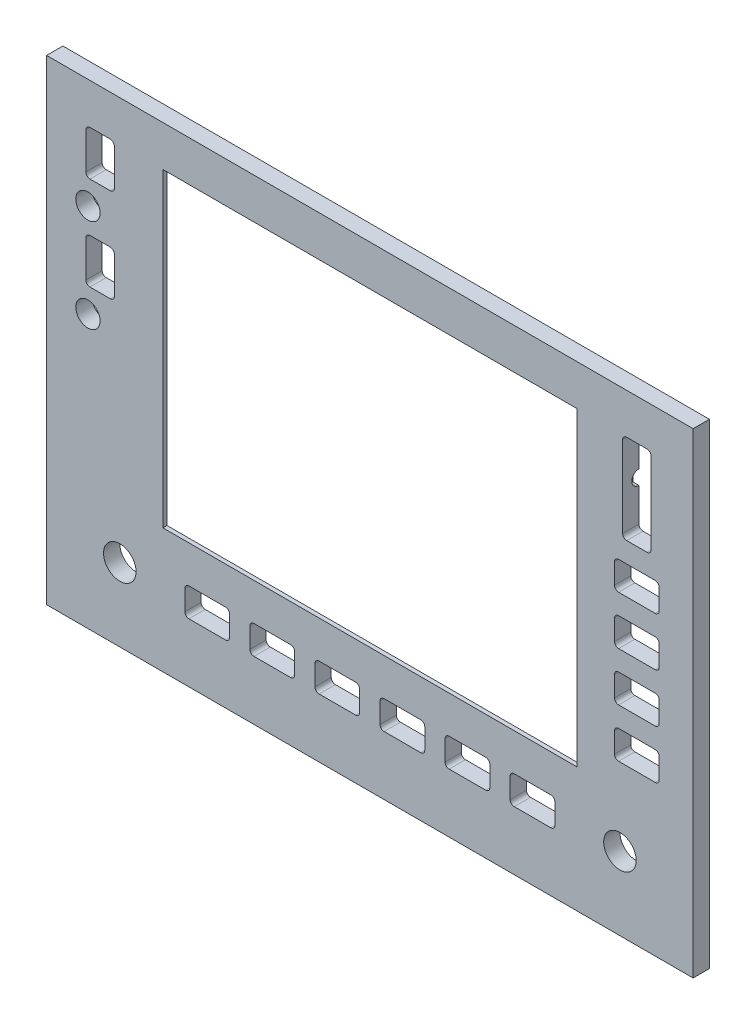
SolidWorks part; units mm, degrees
ref_plane "Plan de face" through (0, 0, 0) normal (0, 0, 1) x (1, 0, 0)
ref_plane "Plan de dessus" through (0, 0, 0) normal (0, 1, 0) x (1, 0, 0)
ref_plane "Plan de droite" through (0, 0, 0) normal (1, 0, 0) x (0, 0, -1)
sketch "Esquisse1" plane through (0, 0, 0) normal (0, 0, 1) x (1, 0, 0)
  line L1 (0, 0) -> (159, 0)
  line L2 (0, 0) -> (0, 117)
  line L3 (0, 117) -> (159, 117)
  line L4 (159, 0) -> (159, 117)
  dimension "D1" = 159
  dimension "D2" = 117
extrude "Boss.-Extru.1" add sketch "Esquisse1" along normal blind 4
sketch "Esquisse3" plane through (0, 0, 4) normal (0, 0, 1) x (1, 0, 0)
  line L1 (28.62, 107) -> (130.38, 107)
  line L2 (28.62, 107) -> (28.62, 30.68)
  line L3 (28.62, 30.68) -> (130.38, 30.68)
  line L4 (130.38, 107) -> (130.38, 30.68)
  line L7 (159, 0) -> (159, 117) construction
  line L8 (0, 117) -> (0, 0) construction
  line L9 (159, 117) -> (0, 117) construction
  dimension "D1" = 101.76
  dimension "D2" = 76.32
  dimension "D3" = 28.62
  dimension "D4" = 28.62
  dimension "D5" = 10
extrude "Enlèv. mat.-Extru.2" cut sketch "Esquisse3" against normal blind 4
sketch "Esquisse9" plane through (0, 0, 0) normal (0, 0, -1) x (-1, 0, 0)
  line L1 (-138.164, 111.6266) -> (-20.164, 111.6266)
  line L2 (-138.164, 111.6266) -> (-138.164, 22.7266)
  line L3 (-138.164, 22.7266) -> (-20.164, 22.7266)
  line L4 (-20.164, 111.6266) -> (-20.164, 22.7266)
  dimension "D5" = 118
  dimension "D6" = 88.9
extrude "Enlèv. mat.-Extru.5" cut sketch "Esquisse9" against normal blind 3
sketch "Esquisse4" plane through (0, 0, 4) normal (0, 0, 1) x (1, 0, 0)
  line L1 (159, 0) -> (159, 117) construction
  line L3 (0, 117) -> (0, 0) construction
  line L4 (0, 0) -> (159, 0) construction
  circle A0 centre (141, 18) radius 4
  circle A1 centre (18, 18) radius 4
  dimension "D1" = 8
  dimension "D2" = 8
  dimension "D3" = 18
  dimension "D4" = 18
  dimension "D5" = 18
  dimension "D6" = 18
extrude "Enlèv. mat.-Extru.3" cut sketch "Esquisse4" against normal blind 4
sketch "Esquisse10" plane through (0, 0, 0) normal (0, 0, -1) x (-1, 0, 0)
  line L0 (-172.9105, 18) -> (39.4334, 18) construction
  line L1 (-159, 0) -> (-159, 117) construction
  line L2 (-124, 21.5) -> (-115, 21.5)
  line L3 (-125, 20.5) -> (-125, 15.5)
  line L4 (-124, 14.5) -> (-115, 14.5)
  line L5 (-114, 20.5) -> (-114, 15.5)
  line L6 (-108, 21.5) -> (-99, 21.5)
  line L7 (-109, 20.5) -> (-109, 15.5)
  line L8 (-108, 14.5) -> (-99, 14.5)
  line L9 (-98, 20.5) -> (-98, 15.5)
  line L10 (-92, 21.5) -> (-83, 21.5)
  line L11 (-93, 20.5) -> (-93, 15.5)
  line L12 (-92, 14.5) -> (-83, 14.5)
  line L13 (-82, 20.5) -> (-82, 15.5)
  line L14 (-76, 21.5) -> (-67, 21.5)
  line L15 (-77, 20.5) -> (-77, 15.5)
  line L16 (-76, 14.5) -> (-67, 14.5)
  line L17 (-66, 20.5) -> (-66, 15.5)
  line L18 (-60, 21.5) -> (-51, 21.5)
  line L19 (-61, 20.5) -> (-61, 15.5)
  line L20 (-60, 14.5) -> (-51, 14.5)
  line L21 (-50, 20.5) -> (-50, 15.5)
  line L22 (-44, 21.5) -> (-35, 21.5)
  line L23 (-45, 20.5) -> (-45, 15.5)
  line L24 (-44, 14.5) -> (-35, 14.5)
  line L25 (-34, 20.5) -> (-34, 15.5)
  line L26 (0, 117) -> (0, 0) construction
  line L27 (0, 0) -> (-159, 0) construction
  line L28 (-145.164, 118.9934) -> (-145.164, 24.726) construction
  line L30 (-147.664, 107) -> (-142.664, 107)
  line L31 (-148.664, 106) -> (-148.664, 86)
  line L32 (-147.664, 85) -> (-142.664, 85)
  line L33 (-141.664, 106) -> (-141.664, 86)
  line L34 (-130.38, 107) -> (-28.62, 107) construction
  line L35 (-13.164, 118.9934) -> (-13.164, 30.4767) construction
  line L36 (-149.664, 80) -> (-140.664, 80)
  line L37 (-150.664, 79) -> (-150.664, 74)
  line L38 (-149.664, 73) -> (-140.664, 73)
  line L39 (-139.664, 79) -> (-139.664, 74)
  line L40 (-149.664, 68) -> (-140.664, 68)
  line L41 (-150.664, 67) -> (-150.664, 62)
  line L42 (-149.664, 61) -> (-140.664, 61)
  line L43 (-139.664, 67) -> (-139.664, 62)
  line L44 (-149.664, 56) -> (-140.664, 56)
  line L45 (-150.664, 55) -> (-150.664, 50)
  line L46 (-149.664, 49) -> (-140.664, 49)
  line L47 (-139.664, 55) -> (-139.664, 50)
  line L48 (-149.664, 44) -> (-140.664, 44)
  line L49 (-150.664, 43) -> (-150.664, 38)
  line L50 (-149.664, 37) -> (-140.664, 37)
  line L51 (-139.664, 43) -> (-139.664, 38)
  line L52 (-138.164, 111.6266) -> (-138.164, 22.7266) construction
  line L53 (-20.164, 22.7266) -> (-20.164, 111.6266) construction
  line L55 (-15.664, 107) -> (-10.664, 107)
  line L56 (-16.664, 106) -> (-16.664, 97)
  line L57 (-15.664, 96) -> (-10.664, 96)
  line L58 (-9.664, 106) -> (-9.664, 97)
  line L59 (-15.664, 84) -> (-10.664, 84)
  line L60 (-16.664, 83) -> (-16.664, 74)
  line L61 (-15.664, 73) -> (-10.664, 73)
  line L62 (-9.664, 83) -> (-9.664, 74)
  arc A0 (-45, 15.5) -> (-44, 14.5) centre (-44, 15.5) ccw
  arc A1 (-35, 21.5) -> (-34, 20.5) centre (-35, 20.5) cw
  arc A2 (-35, 14.5) -> (-34, 15.5) centre (-35, 15.5) ccw
  arc A3 (-44, 21.5) -> (-45, 20.5) centre (-44, 20.5) ccw
  arc A4 (-51, 21.5) -> (-50, 20.5) centre (-51, 20.5) cw
  arc A5 (-51, 14.5) -> (-50, 15.5) centre (-51, 15.5) ccw
  arc A6 (-61, 15.5) -> (-60, 14.5) centre (-60, 15.5) ccw
  arc A7 (-60, 21.5) -> (-61, 20.5) centre (-60, 20.5) ccw
  arc A8 (-67, 21.5) -> (-66, 20.5) centre (-67, 20.5) cw
  arc A9 (-67, 14.5) -> (-66, 15.5) centre (-67, 15.5) ccw
  arc A10 (-77, 15.5) -> (-76, 14.5) centre (-76, 15.5) ccw
  arc A11 (-76, 21.5) -> (-77, 20.5) centre (-76, 20.5) ccw
  arc A12 (-83, 21.5) -> (-82, 20.5) centre (-83, 20.5) cw
  arc A13 (-83, 14.5) -> (-82, 15.5) centre (-83, 15.5) ccw
  arc A14 (-93, 15.5) -> (-92, 14.5) centre (-92, 15.5) ccw
  arc A15 (-92, 21.5) -> (-93, 20.5) centre (-92, 20.5) ccw
  arc A16 (-99, 21.5) -> (-98, 20.5) centre (-99, 20.5) cw
  arc A17 (-99, 14.5) -> (-98, 15.5) centre (-99, 15.5) ccw
  arc A18 (-109, 15.5) -> (-108, 14.5) centre (-108, 15.5) ccw
  arc A19 (-108, 21.5) -> (-109, 20.5) centre (-108, 20.5) ccw
  arc A20 (-115, 21.5) -> (-114, 20.5) centre (-115, 20.5) cw
  arc A21 (-115, 14.5) -> (-114, 15.5) centre (-115, 15.5) ccw
  arc A22 (-125, 15.5) -> (-124, 14.5) centre (-124, 15.5) ccw
  arc A23 (-124, 21.5) -> (-125, 20.5) centre (-124, 20.5) ccw
  arc A24 (-149.664, 44) -> (-150.664, 43) centre (-149.664, 43) ccw
  arc A25 (-150.664, 38) -> (-149.664, 37) centre (-149.664, 38) ccw
  arc A26 (-140.664, 37) -> (-139.664, 38) centre (-140.664, 38) ccw
  arc A27 (-140.664, 44) -> (-139.664, 43) centre (-140.664, 43) cw
  arc A28 (-140.664, 56) -> (-139.664, 55) centre (-140.664, 55) cw
  arc A29 (-140.664, 49) -> (-139.664, 50) centre (-140.664, 50) ccw
  arc A30 (-150.664, 50) -> (-149.664, 49) centre (-149.664, 50) ccw
  arc A31 (-149.664, 56) -> (-150.664, 55) centre (-149.664, 55) ccw
  arc A32 (-149.664, 68) -> (-150.664, 67) centre (-149.664, 67) ccw
  arc A33 (-150.664, 62) -> (-149.664, 61) centre (-149.664, 62) ccw
  arc A34 (-140.664, 61) -> (-139.664, 62) centre (-140.664, 62) ccw
  arc A35 (-140.664, 68) -> (-139.664, 67) centre (-140.664, 67) cw
  arc A36 (-140.664, 73) -> (-139.664, 74) centre (-140.664, 74) ccw
  arc A37 (-140.664, 80) -> (-139.664, 79) centre (-140.664, 79) cw
  arc A38 (-150.664, 74) -> (-149.664, 73) centre (-149.664, 74) ccw
  arc A39 (-149.664, 80) -> (-150.664, 79) centre (-149.664, 79) ccw
  arc A40 (-148.664, 86) -> (-147.664, 85) centre (-147.664, 86) ccw
  arc A41 (-142.664, 85) -> (-141.664, 86) centre (-142.664, 86) ccw
  arc A42 (-142.664, 107) -> (-141.664, 106) centre (-142.664, 106) cw
  arc A43 (-147.664, 107) -> (-148.664, 106) centre (-147.664, 106) ccw
  circle A44 centre (-10.164, 90) radius 3
  circle A45 centre (-10.164, 67) radius 3
  arc A46 (-10.664, 84) -> (-9.664, 83) centre (-10.664, 83) cw
  arc A47 (-10.664, 73) -> (-9.664, 74) centre (-10.664, 74) ccw
  arc A48 (-16.664, 74) -> (-15.664, 73) centre (-15.664, 74) ccw
  arc A49 (-15.664, 84) -> (-16.664, 83) centre (-15.664, 83) ccw
  arc A50 (-10.664, 96) -> (-9.664, 97) centre (-10.664, 97) ccw
  arc A51 (-10.664, 107) -> (-9.664, 106) centre (-10.664, 106) cw
  arc A52 (-15.664, 107) -> (-16.664, 106) centre (-15.664, 106) ccw
  arc A53 (-16.664, 97) -> (-15.664, 96) centre (-15.664, 97) ccw
  point P34 (-45, 14.5)
  point P39 (-34, 14.5)
  point P46 (-50, 14.5)
  point P49 (-61, 14.5)
  point P56 (-66, 14.5)
  point P59 (-77, 14.5)
  point P66 (-82, 14.5)
  point P69 (-93, 14.5)
  point P76 (-98, 14.5)
  point P79 (-109, 14.5)
  point P116 (-150.664, 44)
  point P119 (-150.664, 37)
  point P138 (-139.664, 61)
  point P141 (-139.664, 68)
  point P178 (-9.664, 84)
  point P181 (-9.664, 73)
  dimension "D27" = 1
  dimension "D43" = 1
  dimension "D59" = 6
  dimension "D62" = 6
  dimension "D64" = 1
  dimension "D1" = 3.5
  dimension "D2" = 3.5
  dimension "D3" = 11
  dimension "D4" = 11
  dimension "D5" = 11
  dimension "D6" = 11
  dimension "D7" = 11
  dimension "D8" = 11
  dimension "D9" = 3.5
  dimension "D10" = 3.5
  dimension "D11" = 3.5
  dimension "D12" = 3.5
  dimension "D13" = 3.5
  dimension "D14" = 3.5
  dimension "D15" = 3.5
  dimension "D16" = 3.5
  dimension "D17" = 3.5
  dimension "D18" = 3.5
  dimension "D19" = 34
  dimension "D20" = 5
  dimension "D21" = 5
  dimension "D22" = 5
  dimension "D23" = 5
  dimension "D24" = 5
  dimension "D25" = 34
  dimension "D26" = 18
  dimension "D28" = 3.5
  dimension "D29" = 3.5
  dimension "D30" = 22
  dimension "D31" = 0
  dimension "D32" = 5.5
  dimension "D33" = 5.5
  dimension "D34" = 7
  dimension "D35" = 5
  dimension "D36" = 5.5
  dimension "D37" = 7
  dimension "D38" = 7
  dimension "D39" = 5
  dimension "D40" = 5
  dimension "D41" = 7
  dimension "D42" = 5
  dimension "D44" = 7
  dimension "D45" = 5.5
  dimension "D46" = 5.5
  dimension "D47" = 5.5
  dimension "D48" = 5.5
  dimension "D49" = 7
  dimension "D50" = 5.5
  dimension "D51" = 3.5
  dimension "D52" = 3.5
  dimension "D53" = 11
  dimension "D54" = 0
  dimension "D55" = 12
  dimension "D56" = 3.5
  dimension "D57" = 3.5
  dimension "D58" = 11
  dimension "D60" = 6
  dimension "D61" = 3
  dimension "D63" = 6
extrude "Enlèv. mat.-Extru.6" cut sketch "Esquisse10" against normal blind 4
sketch "Esquisse11" plane through (148.664, 0, 0) normal (-1, 0, 0) x (0, 0, 1)
  line L0 (0, 106) -> (0, 86) construction
  line L1 (4, 107) -> (0, 107) construction
  line L2 (4, 85) -> (0, 85) construction
  circle A0 centre (0, 96) radius 1.75
  dimension "D1" = 3.5
  dimension "D2" = 11
  dimension "D3" = 11
extrude "Enlèv. mat.-Extru.7" cut sketch "Esquisse11" against normal blind 1.5 and the other way blind 8.5
